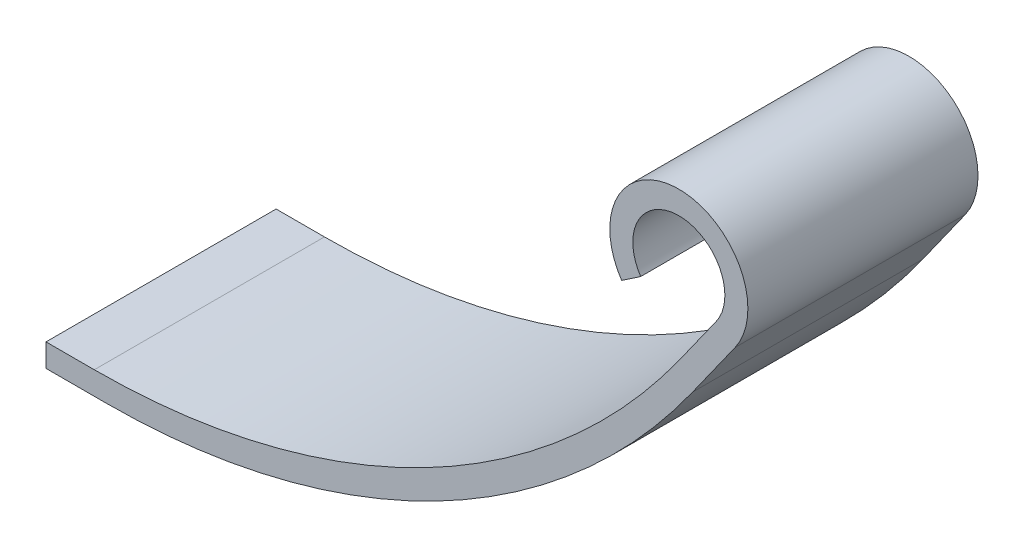
SolidWorks part; units mm, degrees
ref_plane "Front Plane" through (0, 0, 0) normal (0, 0, 1) x (1, 0, 0)
ref_plane "Top Plane" through (0, 0, 0) normal (0, 1, 0) x (1, 0, 0)
ref_plane "Right Plane" through (0, 0, 0) normal (1, 0, 0) x (0, 0, -1)
sketch "Sketch1" plane through (0, 0, 0) normal (0, 0, 1) x (1, 0, 0)
  line L0 (0, 0) -> (15, 0)
  line L1 (15, 0) -> (23.9567, 12.6102)
  line L2 (0, 0) -> (0, 0.8)
  line L3 (0, 0.8) -> (14.587, 0.8)
  line L4 (14.587, 0.8) -> (23.3044, 13.0735)
  line L5 (20.6746, 13.1037) -> (20.0119, 12.6556)
  arc A0 (23.9567, 12.6102) -> (20.0119, 12.6556) centre (22, 14) ccw
  arc A1 (23.3044, 13.0735) -> (20.6746, 13.1037) centre (22, 14) ccw
  dimension "D3" = 1.6
  dimension "D1" = 0.8
  dimension "D2" = 0.8
  dimension "D4" = 22
  dimension "D5" = 15
  dimension "D6" = 14
extrude "Boss-Extrude1" add sketch "Sketch1" along normal blind 8
fillet "Fillet1" radius 25 2 edges at (15, 0, 4) (14.587, 0.8, 4)
